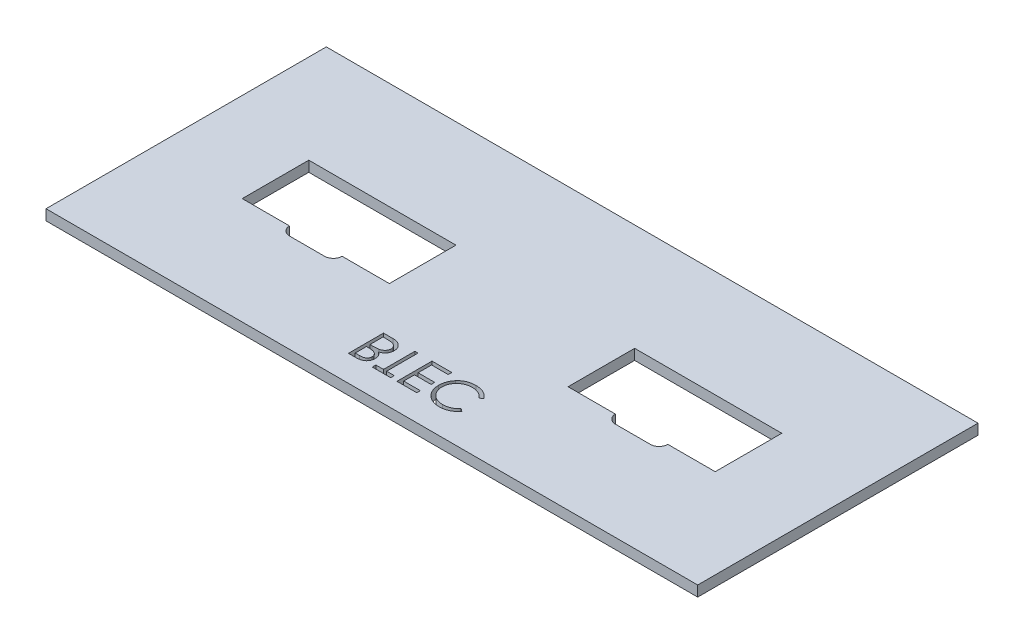
SolidWorks part; units mm, degrees
ref_plane "Front Plane" through (0, 0, 0) normal (0, 0, 1) x (1, 0, 0)
ref_plane "Top Plane" through (0, 0, 0) normal (0, 1, 0) x (1, 0, 0)
ref_plane "Right Plane" through (0, 0, 0) normal (1, 0, 0) x (0, 0, -1)
sketch "Esquisse1" plane through (0, 0, 0) normal (0, 1, 0) x (1, 0, 0)
  line L0 (0, 40) -> (0, -40) construction
  line L1 (93, -40) -> (-93, -40)
  line L2 (93, -40) -> (93, 40)
  line L3 (93, 40) -> (-93, 40)
  line L4 (-93, -40) -> (-93, 40)
  line L7 (0, -40) -> (-93, 40) construction
  line L8 (-93, -40) -> (0, 40) construction
  line L9 (0, 40) -> (93, -40) construction
  line L10 (0, -40) -> (93, 40) construction
  line L12 (-25.5, -9.5) -> (-67.5, -9.5)
  line L13 (-25.5, -9.5) -> (-25.5, 9.5)
  line L14 (-25.5, 9.5) -> (-67.5, 9.5)
  line L15 (-67.5, -9.5) -> (-67.5, 9.5)
  line L16 (-25.5, -9.5) -> (-67.5, 9.5) construction
  line L17 (-25.5, 9.5) -> (-67.5, -9.5) construction
  line L18 (67.5, -9.5) -> (25.5, -9.5)
  line L19 (67.5, -9.5) -> (67.5, 9.5)
  line L20 (67.5, 9.5) -> (25.5, 9.5)
  line L21 (25.5, -9.5) -> (25.5, 9.5)
  line L22 (67.5, -9.5) -> (25.5, 9.5) construction
  line L23 (67.5, 9.5) -> (25.5, -9.5) construction
  point P0 (0, 0)
  point P8 (-46.5, 0)
  point P13 (46.5, 0)
  dimension "D1" = 186
  dimension "D2" = 80
  dimension "D3" = 42
  dimension "D4" = 19
  dimension "D5" = 42
  dimension "D6" = 19
extrude "Boss.-Extru.1" add sketch "Esquisse1" along normal blind 3
sketch "Esquisse3" plane through (0, 3, 0) normal (0, 1, 0) x (1, 0, 0)
  line L0 (-67.5, -9.5) -> (-25.5, -9.5) construction
  line L4 (0, 40) -> (0, 19.4882)
  line L5 (93, 40) -> (-93, 40) construction
  line L6 (25.5, -9.5) -> (67.5, -9.5) construction
  line L9 (-78.821, 0) -> (81.9082, 0)
  line L10 (41.5, -9.5) -> (51.5, -9.5) construction
  line L11 (41.5, -7) -> (51.5, -7)
  line L12 (41.5, -12) -> (51.5, -12)
  line L13 (-41.5, -9.5) -> (-51.5, -9.5) construction
  line L14 (-41.5, -7) -> (-51.5, -7)
  line L15 (-41.5, -12) -> (-51.5, -12)
  arc A4 (41.5, -7) -> (41.5, -12) centre (41.5, -9.5) ccw
  arc A5 (51.5, -12) -> (51.5, -7) centre (51.5, -9.5) ccw
  arc A6 (-41.5, -7) -> (-41.5, -12) centre (-41.5, -9.5) cw
  arc A7 (-51.5, -12) -> (-51.5, -7) centre (-51.5, -9.5) cw
  point P25 (46.5, -9.5)
  point P32 (-46.5, -9.5)
  line M6 (-25.5, -9.5) -> (-67.5, -9.5)
  line M10 (67.5, -9.5) -> (25.5, -9.5)
  dimension "D3" = 2.5
  dimension "D4" = 2.5
  dimension "D1" = 10
  dimension "D2" = 10
extrude "Enlèv. mat.-Extru.3" cut sketch "Esquisse3" against normal blind 10 contours A7 L15 A6 M6 | A7 A6 L14 M6 | L12 A5 A4 M10
sketch "Esquisse2" plane through (0, 3, 0) normal (0, 1, 0) x (1, 0, 0)
  line L0 (-67.5, -9.5) -> (-54, -9.5) construction
  line L1 (-26, -15.5) -> (-67, -15.5)
  line L2 (-26, -15.5) -> (-26, -10.5)
  line L4 (-67, -15.5) -> (-67, -10.5)
  line L5 (-26, -15.5) -> (-60.75, -9.5) construction
  line L6 (-60.75, -9.5) -> (-67, -15.5) construction
  line L7 (25.5, -9.5) -> (67.5, -9.5)
  line L8 (25.5, -9.5) -> (39, -9.5) construction
  line L9 (67.5, -15.5) -> (25.5, -15.5)
  line L10 (67.5, -15.5) -> (67.5, -9.5)
  line L12 (25.5, -15.5) -> (25.5, -9.5)
  line L13 (67.5, -15.5) -> (32.25, -9.5) construction
  line L14 (32.25, -9.5) -> (25.5, -15.5) construction
  line L16 (-67, -10.5) -> (-26, -10.5)
  point P0 (-60.75, -9.5)
  point P9 (32.25, -9.5)
sketch "Esquisse4" plane through (0, 3, 0) normal (0, 1, 0) x (1, 0, 0)
  line L0 (-38.6869, -22.5754) -> (40.2305, -22.5754) construction
  text T0 "BTEC" font "Century Gothic" height 10
extrude "Enlèv. mat.-Extru.4" cut sketch "Esquisse4" against normal blind 10
sketch "Esquisse6" plane through (0, 0, 0) normal (0, -1, 0) x (1, 0, 0)
  line L0 (-25.5, -9.5) -> (25.5, -9.5) construction
  text T0 "921" font "Agency FB" height 15
extrude "Boss.-Extru.3" add sketch "Esquisse6" along normal blind 3
